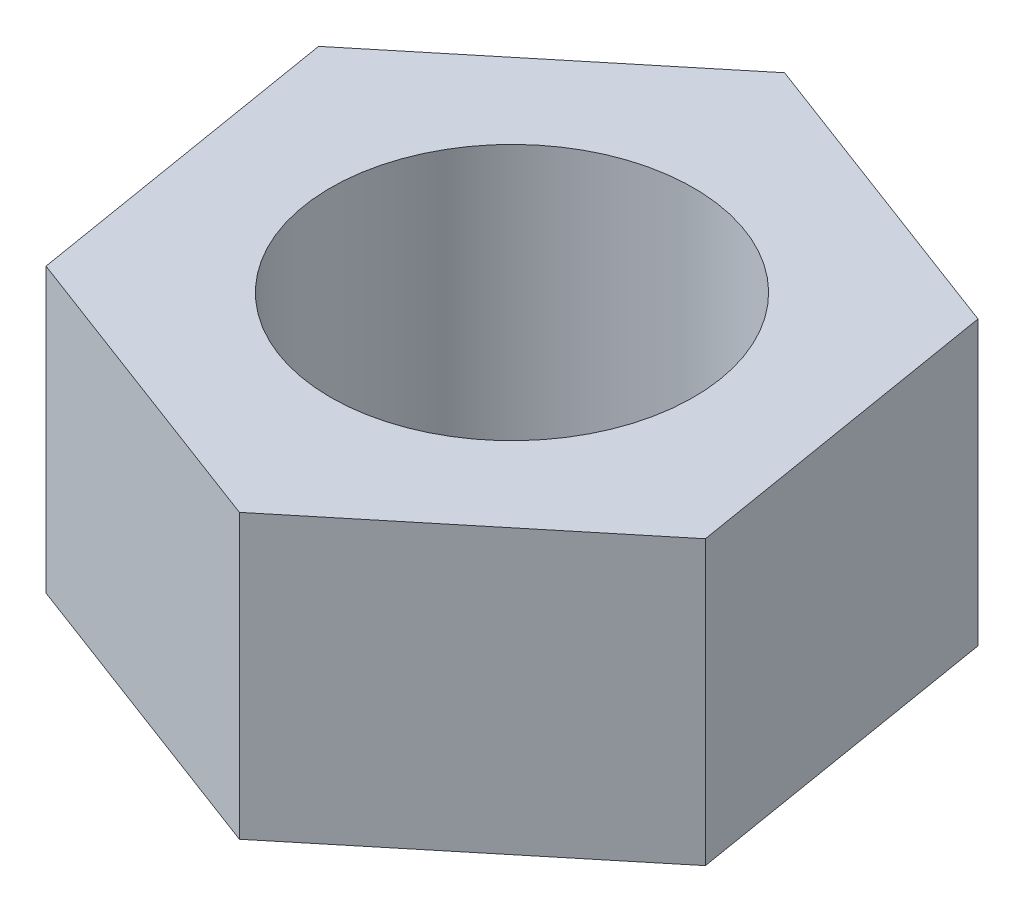
SolidWorks part; units mm, degrees
ref_plane "Front Plane" through (0, 0, 0) normal (0, 0, 1) x (1, 0, 0)
ref_plane "Top Plane" through (0, 0, 0) normal (0, 1, 0) x (1, 0, 0)
ref_plane "Right Plane" through (0, 0, 0) normal (1, 0, 0) x (0, 0, -1)
sketch "Sketch1" plane through (0, 0, 0) normal (0, 1, 0) x (1, 0, 0)
  line L1 (3.5247, 2.8948) -> (-0.7446, 4.4999)
  line L2 (-0.7446, 4.4999) -> (-4.2693, 1.6051)
  line L3 (-4.2693, 1.6051) -> (-3.5247, -2.8948)
  line L4 (-3.5247, -2.8948) -> (0.7446, -4.4999)
  line L5 (0.7446, -4.4999) -> (4.2693, -1.6051)
  line L6 (4.2693, -1.6051) -> (3.5247, 2.8948)
  circle A0 centre (0, 0) radius 3.95 construction
  circle A1 centre (0, 0) radius 2.5
  dimension "D1" = 7.9
  dimension "D2" = 5
extrude "Boss-Extrude1" add sketch "Sketch1" along normal blind 3.9
